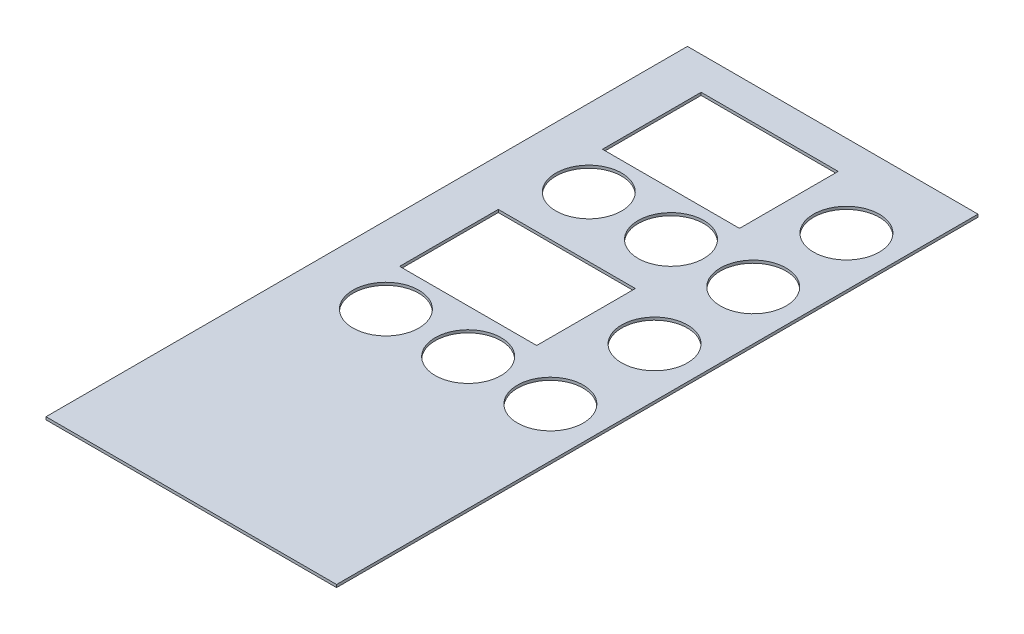
SolidWorks part; units mm, degrees
ref_plane "Спереди" through (0, 0, 0) normal (0, 0, 1) x (1, 0, 0)
ref_plane "Сверху" through (0, 0, 0) normal (0, 1, 0) x (1, 0, 0)
ref_plane "Справа" through (0, 0, 0) normal (1, 0, 0) x (0, 0, -1)
sketch "Эскиз1" plane through (0, 0, 0) normal (0, 1, 0) x (1, 0, 0)
  line L1 (-26.5, -58.5) -> (26.5, -58.5)
  line L2 (-26.5, -58.5) -> (-26.5, 58.5)
  line L3 (-26.5, 58.5) -> (26.5, 58.5)
  line L4 (26.5, -58.5) -> (26.5, 58.5)
  line L5 (-26.5, -58.5) -> (26.5, 58.5) construction
  line L6 (-26.5, 58.5) -> (26.5, -58.5) construction
  point P0 (0, 0)
  dimension "D1" = 117
  dimension "D2" = 53
extrude "Бобышка-Вытянуть1" add sketch "Эскиз1" along normal blind 0.5
sketch "Эскиз2" plane through (0, 0.5, 0) normal (0, 1, 0) x (1, 0, 0)
  line L0 (-26.5, 55.5) -> (26.5, 55.5) construction
  line L1 (-26.5, 58.5) -> (-26.5, -58.5) construction
  line L2 (26.5, -58.5) -> (26.5, 58.5) construction
  line L3 (26.5, 58.5) -> (-26.5, 58.5) construction
  line L4 (0, 58.5) -> (0, -58.5) construction
  line L5 (-18, 52.5) -> (7, 52.5)
  line L6 (-18, 52.5) -> (-18, 34.5)
  line L7 (-18, 34.5) -> (7, 34.5)
  line L8 (7, 52.5) -> (7, 34.5)
  line L9 (-18, 52.5) -> (7, 34.5) construction
  line L10 (-18, 34.5) -> (7, 52.5) construction
  line L11 (-26.5, -58.5) -> (26.5, -58.5) construction
  line L13 (-18, -2.5) -> (7, -2.5)
  line L14 (-18, -2.5) -> (-18, 15.5)
  line L15 (-18, 15.5) -> (7, 15.5)
  line L16 (7, -2.5) -> (7, 15.5)
  line L17 (-18, -2.5) -> (7, 15.5) construction
  line L18 (-18, 15.5) -> (7, -2.5) construction
  point P8 (-5.5, 43.5)
  point P17 (-5.5, 6.5)
  dimension "D1" = 3
  dimension "D2" = 3
  dimension "D3" = 18
  dimension "D4" = 25
  dimension "D5" = 18
  dimension "D6" = 18
  dimension "D7" = 19
extrude "Вырез-Вытянуть1" cut sketch "Эскиз2" against normal through all
sketch "Эскиз4" plane through (0, 0.5, 0) normal (0, 1, 0) x (1, 0, 0)
  line L0 (-26.5, 55.5) -> (26.5, 55.5) construction
  line L1 (-26.5, 58.5) -> (-26.5, -58.5) construction
  line L2 (26.5, -58.5) -> (26.5, 58.5) construction
  line L3 (26.5, 58.5) -> (-26.5, 58.5) construction
  line L4 (0, 58.5) -> (0, -58.5) construction
  line L5 (-26.5, -58.5) -> (26.5, -58.5) construction
  circle A0 centre (17.5, 43.5) radius 6
  circle A1 centre (17.5, 26.5) radius 6
  circle A2 centre (17.5, 8.5) radius 6
  circle A3 centre (17.5, -10.5) radius 6
  circle A4 centre (2.5, 26.5) radius 6
  circle A5 centre (-12.5, 26.5) radius 6
  circle A6 centre (2.5, -10.5) radius 6
  circle A7 centre (-12.5, -10.5) radius 6
  dimension "D4" = 17
  dimension "отверстие под кнопку" = 12
  dimension "D5" = 18
  dimension "D1" = 3
  dimension "D2" = 12
  dimension "D3" = 17.5
  dimension "D6" = 19
  dimension "D7" = 15
  dimension "D8" = 15
extrude "Вырез-Вытянуть2" cut sketch "Эскиз4" against normal through all
